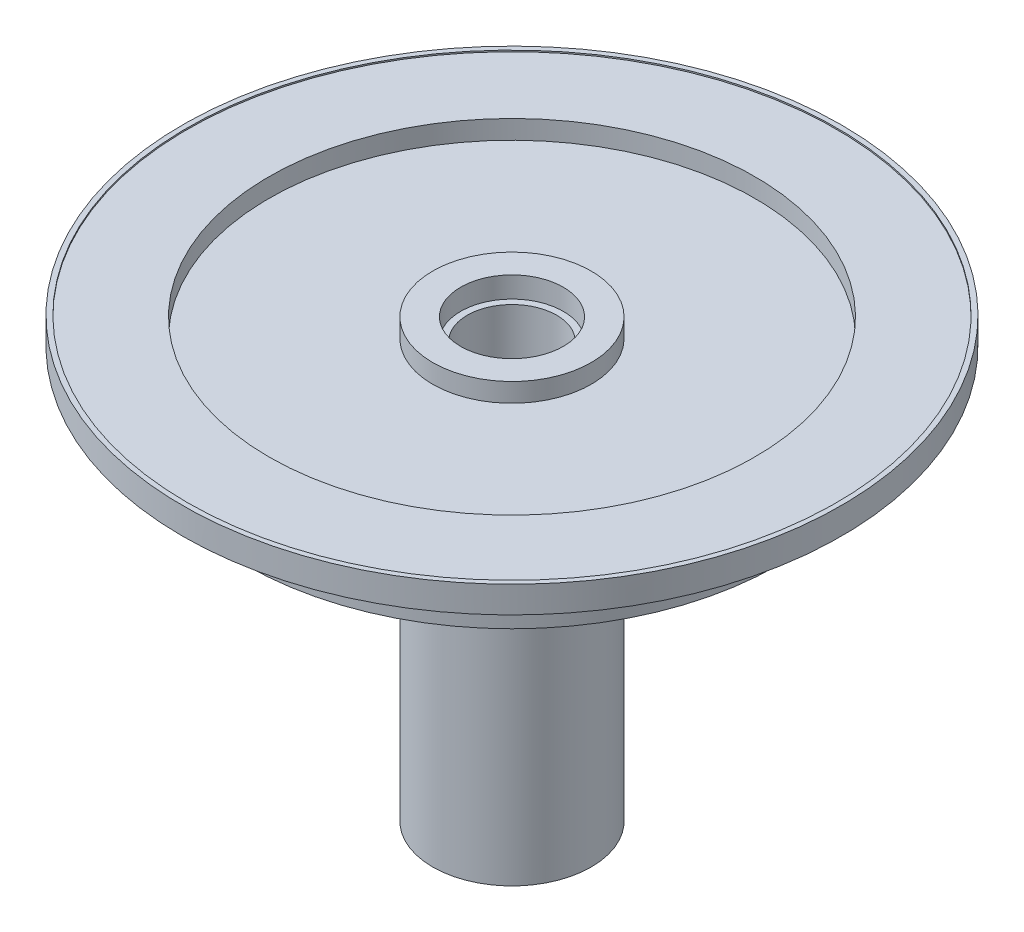
SolidWorks part; units mm, degrees
material "AISI 316 Stainless Steel Sheet (SS)"
ref_plane "Front Plane" through (0, 0, 0) normal (0, 0, 1) x (1, 0, 0)
ref_plane "Top Plane" through (0, 0, 0) normal (0, 1, 0) x (1, 0, 0)
ref_plane "Right Plane" through (0, 0, 0) normal (1, 0, 0) x (0, 0, -1)
sketch "Sketch1" plane through (0, 0, 0) normal (0, 1, 0) x (1, 0, 0)
  circle A0 centre (0, 0) radius 38.1
  dimension "D1" = 76.2
extrude "Boss-Extrude1" add sketch "Sketch1" along normal blind 4.826
sketch "Sketch2" plane through (0, 4.826, 0) normal (0, 1, 0) x (1, 0, 0)
  circle A0 centre (0, 0) radius 38.1 construction
  circle A1 centre (0, 0) radius 38.1
extrude "Boss-Extrude2" add sketch "Sketch2" along normal blind 3.302 draft 70 draft outward yes
sketch "Sketch3" plane through (0, 8.128, 0) normal (0, 1, 0) x (1, 0, 0)
  circle A0 centre (0, 0) radius 47.1722 construction
  circle A1 centre (0, 0) radius 47.1722
extrude "Boss-Extrude3" add sketch "Sketch3" along normal blind 3.81
sketch "Sketch4" plane through (0, 11.938, 0) normal (0, 1, 0) x (1, 0, 0)
  circle A3 centre (0, 0) radius 46.4722
  circle A4 centre (0, 0) radius 46.4722
  dimension "D1" = 0.7
extrude "Cut-Extrude1" cut sketch "Sketch4" against normal blind 0.2
sketch "Sketch6" plane through (0, 11.738, 0) normal (0, 1, 0) x (1, 0, 0)
  circle A1 centre (0, 0) radius 11.35
  circle A2 centre (0, 0) radius 34.7722
  circle A3 centre (0, 0) radius 34.7722
  dimension "D2" = 22.7
  dimension "D1" = 11.7
extrude "Cut-Extrude2" cut sketch "Sketch6" against normal blind 2.7
sketch "Sketch7" plane through (0, 11.738, 0) normal (0, 1, 0) x (1, 0, 0)
  circle A0 centre (0, 0) radius 5.35
  dimension "D1" = 10.7
extrude "Cut-Extrude3" cut sketch "Sketch7" against normal through all
sketch "Sketch8" plane through (0, 0, 0) normal (0, -1, 0) x (1, 0, 0)
  circle A0 centre (0, 0) radius 11.35
  circle A1 centre (0, 0) radius 5.35 construction
  circle A2 centre (0, 0) radius 5.35
  dimension "D1" = 22.7
extrude "Boss-Extrude4" add sketch "Sketch8" along normal blind 50.8
sketch "Sketch9" plane through (0, -50.8, 0) normal (0, -1, 0) x (1, 0, 0)
  circle A0 centre (0, 0) radius 7.35
  dimension "D1" = 14.7
extrude "Cut-Extrude4" cut sketch "Sketch9" against normal blind 3
sketch "Sketch10" plane through (0, 11.738, 0) normal (0, 1, 0) x (1, 0, 0)
  circle A0 centre (0, 0) radius 7.35
  dimension "D1" = 14.7
extrude "Cut-Extrude5" cut sketch "Sketch10" against normal blind 3
sketch "Sketch11" plane through (0, 0, 0) normal (0, -1, 0) x (1, 0, 0)
  circle A0 centre (0, 0) radius 6.4
  dimension "D1" = 12.8
ref_plane "Plane1" through (0, -35.8, 0) normal (0, -1, 0) x (-1, 0, 0)
ref_plane "Plane2" through (0, -30.8, 0) normal (0, -1, 0) x (-1, 0, 0)
sketch "Sketch12" plane through (0, -35.8, 0) normal (0, -1, 0) x (-1, 0, 0)
  circle A0 centre (0, 0) radius 6.4 construction
  circle A1 centre (0, 0) radius 6.4
extrude "Cut-Extrude8" cut sketch "Sketch12" along normal through all
sketch "Sketch13" plane through (0, -30.8, 0) normal (0, -1, 0) x (-1, 0, 0)
  circle A0 centre (0, 0) radius 6.4 construction
  circle A1 centre (0, 0) radius 6.4
extrude "Cut-Extrude9" cut sketch "Sketch13" against normal through all
